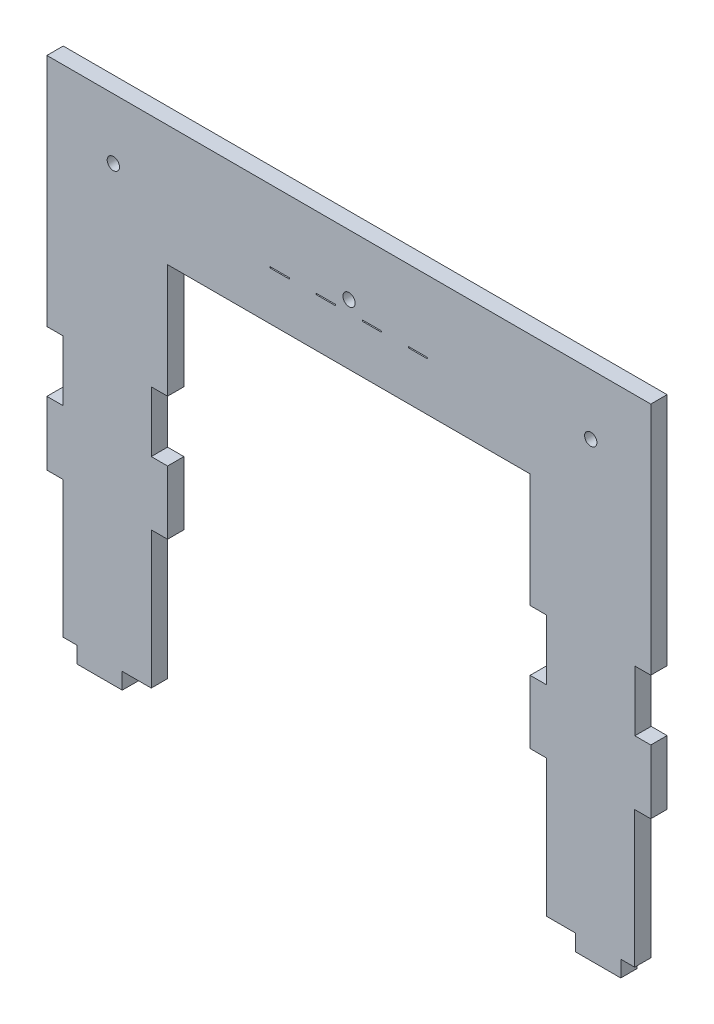
SolidWorks part; units mm, degrees
ref_plane "Front Plane" through (0, 0, 0) normal (0, 0, 1) x (1, 0, 0)
ref_plane "Top Plane" through (0, 0, 0) normal (0, 1, 0) x (1, 0, 0)
ref_plane "Right Plane" through (0, 0, 0) normal (1, 0, 0) x (0, 0, -1)
sketch "Sketch1" plane through (0, 0, 0) normal (0, 0, 1) x (1, 0, 0)
  line L0 (-34.5174, -9.4807) -> (-34.5174, 13.2011)
  line L1 (-34.5174, 13.2011) -> (-31.8174, 13.2011)
  line L2 (-31.8174, 13.2011) -> (-31.8174, 23.7011)
  line L3 (-31.8174, 23.7011) -> (-34.5174, 23.7011)
  line L4 (-34.5174, 23.7011) -> (-34.5174, 33.7011)
  line L5 (-34.5174, 33.7011) -> (-31.8174, 33.7011)
  line L6 (-31.8174, 33.7011) -> (-31.8174, 52.5613)
  line L7 (-51.785, 72.5613) -> (48.1502, 72.5613)
  line L8 (-1.8174, 52.5613) -> (-1.8174, 3.2011) construction
  line L9 (-34.5174, -9.4807) -> (-39.3174, -9.4807)
  line L10 (-39.3174, -9.4807) -> (-39.3174, -12.1807)
  line L11 (-39.3174, -12.1807) -> (-46.8174, -12.1807)
  line L12 (-46.8174, -12.1807) -> (-46.8174, -9.4807)
  line L13 (-46.8174, -9.4807) -> (-49.1174, -9.4807)
  line L14 (-51.785, 13.1219) -> (-51.785, 23.7011)
  line L15 (-31.8174, 52.5613) -> (28.1826, 52.5613)
  line L16 (9.6126, 60.5613) -> (-13.2474, 60.5613) construction
  line L17 (-11.6599, 60.7613) -> (-14.8349, 60.7613)
  line L18 (-11.6599, 60.7613) -> (-11.6599, 60.5613)
  line L19 (-11.6599, 60.5613) -> (-14.8349, 60.5613)
  line L20 (-14.8349, 60.7613) -> (-14.8349, 60.5613)
  line L21 (-4.0399, 60.7613) -> (-7.2149, 60.7613)
  line L22 (-4.0399, 60.7613) -> (-4.0399, 60.5613)
  line L23 (-4.0399, 60.5613) -> (-7.2149, 60.5613)
  line L24 (-49.1174, 13.1219) -> (-49.1174, -9.4807)
  line L25 (43.1826, -9.4807) -> (45.4826, -9.4807)
  line L26 (43.1826, -12.1807) -> (43.1826, -9.4807)
  line L27 (35.6826, -12.1807) -> (43.1826, -12.1807)
  line L28 (35.6826, -9.4807) -> (35.6826, -12.1807)
  line L29 (30.8826, -9.4807) -> (35.6826, -9.4807)
  line L30 (28.1826, 33.7011) -> (28.1826, 52.5613)
  line L31 (30.8826, 33.7011) -> (28.1826, 33.7011)
  line L32 (30.8826, 23.7011) -> (30.8826, 33.7011)
  line L33 (28.1826, 23.7011) -> (30.8826, 23.7011)
  line L34 (28.1826, 13.2011) -> (28.1826, 23.7011)
  line L35 (30.8826, 13.2011) -> (28.1826, 13.2011)
  line L36 (30.8826, -9.4807) -> (30.8826, 13.2011)
  line L37 (-7.2149, 60.7613) -> (-7.2149, 60.5613)
  line L38 (3.5801, 60.7613) -> (0.4051, 60.7613)
  line L39 (3.5801, 60.7613) -> (3.5801, 60.5613)
  line L40 (3.5801, 60.5613) -> (0.4051, 60.5613)
  line L41 (0.4051, 60.7613) -> (0.4051, 60.5613)
  line L42 (11.2001, 60.7613) -> (8.0251, 60.7613)
  line L43 (11.2001, 60.7613) -> (11.2001, 60.5613)
  line L44 (11.2001, 60.5613) -> (8.0251, 60.5613)
  line L45 (8.0251, 60.7613) -> (8.0251, 60.5613)
  line L46 (-46.785, -12.1807) -> (-39.285, -12.1807) construction
  line L47 (45.515, 23.7011) -> (48.1502, 23.7011)
  line L48 (-51.785, 52.5613) -> (-51.785, 72.5613) construction
  line L49 (48.1502, 33.7011) -> (48.1502, 72.5613)
  line L51 (45.515, 23.7011) -> (45.515, 33.7011)
  line L52 (45.515, 33.7011) -> (48.1502, 33.7011)
  line L53 (45.4826, 13.1219) -> (48.1502, 13.1219)
  line L54 (48.1502, 23.7011) -> (48.1502, 13.1219)
  line L55 (-49.1174, 13.1219) -> (-51.785, 13.1219)
  line L57 (-49.1498, 23.7011) -> (-51.785, 23.7011)
  line L58 (-49.1498, 23.7011) -> (-49.1498, 33.7011)
  line L59 (45.4826, 13.1219) -> (45.4826, -9.4807)
  line L60 (-49.1498, 33.7011) -> (-51.785, 33.7011)
  line L61 (-51.785, 33.7011) -> (-51.785, 72.5613)
  circle A1 centre (-40.7925, 62.5613) radius 1.016
  circle A2 centre (38.215, 62.5613) radius 1.016
  circle A3 centre (-1.785, 62.5613) radius 1.016
  point P20 (-1.8174, 72.5613)
  point P21 (-1.8174, 60.5613)
  point P26 (-1.8174, 72.5613)
  dimension "D4" = 4
  dimension "D1" = 2.7
  dimension "D2" = 30
  dimension "D3" = 30.5
  dimension "D5" = 3.175
  dimension "D6" = 0.2
  dimension "D7" = 20
  dimension "D8" = 8
  dimension "D9" = 2.7
  dimension "D10" = 10
  dimension "D11" = 7.5
  dimension "D12" = 10.5
  dimension "D13" = 22.6818
  dimension "D14" = 18.8602
  dimension "D15" = 10
  dimension "D16" = 10.5792
  dimension "D17" = 4.8
  dimension "D18" = 22.6026
  dimension "D19" = 14.6324
  dimension "D20" = 14.6
extrude "Base" add sketch "Sketch1" along normal blind 2.7
